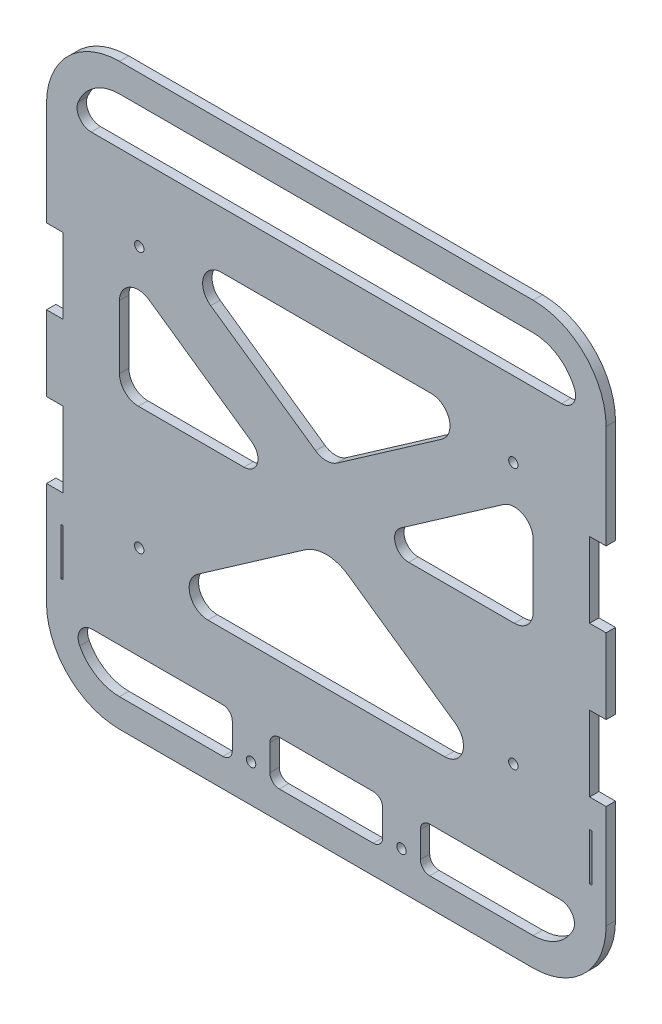
SolidWorks part; units mm, degrees
ref_plane "Front Plane" through (0, 0, 0) normal (0, 0, 1) x (1, 0, 0)
ref_plane "Top Plane" through (0, 0, 0) normal (0, 1, 0) x (1, 0, 0)
ref_plane "Right Plane" through (0, 0, 0) normal (1, 0, 0) x (0, 0, -1)
ref_plane "Plane1" through (0, 0, -676.275) normal (0, 0, 1) x (1, 0, 0)
sketch "Sketch1" plane through (0, 0, -676.275) normal (0, 0, 1) x (1, 0, 0)
  line L0 (94.488, -171.45) -> (94.488, -136.525)
  line L1 (94.488, -136.525) -> (88.9, -136.525)
  line L2 (88.9, -136.525) -> (88.9, -111.125)
  line L3 (88.9, -111.125) -> (94.488, -111.125)
  line L4 (94.488, -111.125) -> (94.488, -85.725)
  line L5 (94.488, -85.725) -> (88.9, -85.725)
  line L6 (88.9, -85.725) -> (88.9, -60.325)
  line L7 (88.9, -60.325) -> (94.488, -60.325)
  line L8 (94.488, -60.325) -> (94.488, -25.4)
  line L9 (69.85, -0.762) -> (-69.85, -0.762)
  line L10 (-94.488, -25.4) -> (-94.488, -60.325)
  line L11 (-94.488, -60.325) -> (-88.9, -60.325)
  line L12 (-88.9, -60.325) -> (-88.9, -85.725)
  line L13 (-88.9, -85.725) -> (-94.488, -85.725)
  line L14 (-94.488, -85.725) -> (-94.488, -111.125)
  line L15 (-94.488, -111.125) -> (-88.9, -111.125)
  line L16 (-88.9, -111.125) -> (-88.9, -136.525)
  line L17 (-88.9, -136.525) -> (-94.488, -136.525)
  line L18 (-94.488, -136.525) -> (-94.488, -171.45)
  line L19 (-69.85, -196.088) -> (69.85, -196.088)
  line L20 (7.2646, -112.3283) -> (43.598, -137.6665)
  line L21 (39.9657, -149.225) -> (-39.9657, -149.225)
  line L22 (-43.598, -137.6665) -> (-7.2646, -112.3283)
  line L23 (39.0453, -56.8078) -> (3.6323, -81.5041)
  line L24 (-3.6323, -81.5041) -> (-39.0453, -56.8078)
  line L25 (-35.4129, -45.2493) -> (35.4129, -45.2493)
  line L26 (69.85, -70.7201) -> (69.85, -92.075)
  line L27 (63.5, -98.425) -> (27.8268, -98.425)
  line L28 (25.1025, -89.7561) -> (59.8677, -65.5116)
  line L29 (-59.8677, -65.5116) -> (-25.1025, -89.7561)
  line L30 (-27.8268, -98.425) -> (-63.5, -98.425)
  line L31 (-69.85, -92.075) -> (-69.85, -70.7201)
  line L32 (0, -0.762) -> (0, -196.088) construction
  line L33 (-63.1655, -51.5993) -> (63.1655, -51.5993) construction
  line L34 (-63.1655, -51.5993) -> (-63.1655, -139.7) construction
  line L35 (-63.1655, -139.7) -> (63.1655, -139.7) construction
  line L36 (63.1655, -51.5993) -> (63.1655, -139.7) construction
  line L37 (-63.1655, -51.5993) -> (63.1655, -139.7) construction
  line L38 (-63.1655, -139.7) -> (63.1655, -51.5993) construction
  line L39 (-69.85, -186.563) -> (-34.925, -186.563)
  line L40 (-79.0397, -171.45) -> (-34.925, -171.45)
  line L41 (-25.4, -183.388) -> (25.4, -183.388) construction
  line L42 (69.85, -10.287) -> (-69.85, -10.287)
  line L43 (-31.75, -174.625) -> (-31.75, -183.388)
  line L44 (-19.05, -183.388) -> (-19.05, -174.625)
  line L45 (19.05, -174.625) -> (19.05, -183.388)
  line L46 (31.75, -174.625) -> (31.75, -183.388)
  line L47 (-15.875, -171.45) -> (15.875, -171.45)
  line L48 (34.925, -171.45) -> (79.0397, -171.45)
  line L49 (-15.875, -186.563) -> (15.875, -186.563)
  line L50 (-69.85, -186.563) -> (69.85, -186.563) construction
  line L51 (34.925, -186.563) -> (69.85, -186.563)
  line L52 (-79.4117, -26.1993) -> (79.4117, -26.1993)
  line L53 (-89.6493, -146.05) -> (-89.6493, -161.925)
  line L54 (88.9, -146.05) -> (89.6493, -146.05)
  line L55 (88.9, -146.05) -> (88.9, -161.925)
  line L56 (88.9, -161.925) -> (89.6493, -161.925)
  line L57 (89.6493, -146.05) -> (89.6493, -161.925)
  line L58 (-88.9, -161.925) -> (-89.6493, -161.925)
  line L59 (-88.9, -146.05) -> (-88.9, -161.925)
  line L60 (-88.9, -146.05) -> (-89.6493, -146.05)
  circle A0 centre (63.1655, -139.7) radius 1.5875
  circle A1 centre (-83.82, -84.8367) radius 1.5875 construction
  circle A2 centre (-63.1655, -51.5993) radius 1.5875
  circle A3 centre (25.4, -183.388) radius 1.5875
  arc A4 (69.85, -196.088) -> (94.488, -171.45) centre (69.85, -171.45) ccw
  arc A5 (94.488, -25.4) -> (69.85, -0.762) centre (69.85, -25.4) ccw
  arc A6 (-69.85, -0.762) -> (-94.488, -25.4) centre (-69.85, -25.4) ccw
  arc A7 (-94.488, -171.45) -> (-69.85, -196.088) centre (-69.85, -171.45) ccw
  circle A8 centre (-25.4, -183.388) radius 1.5875
  arc A9 (43.598, -137.6665) -> (39.9657, -149.225) centre (39.9657, -142.875) cw
  arc A10 (-39.9657, -149.225) -> (-43.598, -137.6665) centre (-39.9657, -142.875) cw
  arc A11 (-7.2646, -112.3283) -> (7.2646, -112.3283) centre (0, -122.7454) cw
  circle A12 centre (-63.1655, -139.7) radius 1.5875
  arc A13 (3.6323, -81.5041) -> (-3.6323, -81.5041) centre (0, -76.2956) cw
  arc A14 (-35.4129, -45.2493) -> (-39.0453, -56.8078) centre (-35.4129, -51.5993) ccw
  arc A15 (35.4129, -45.2493) -> (39.0453, -56.8078) centre (35.4129, -51.5993) cw
  arc A16 (69.85, -92.075) -> (63.5, -98.425) centre (63.5, -92.075) cw
  arc A17 (27.8268, -98.425) -> (25.1025, -89.7561) centre (27.8268, -93.6625) cw
  arc A18 (59.8677, -65.5116) -> (69.85, -70.7201) centre (63.5, -70.7201) cw
  arc A19 (-25.1025, -89.7561) -> (-27.8268, -98.425) centre (-27.8268, -93.6625) cw
  arc A20 (-63.5, -98.425) -> (-69.85, -92.075) centre (-63.5, -92.075) cw
  arc A21 (-69.85, -70.7201) -> (-59.8677, -65.5116) centre (-63.5, -70.7201) cw
  circle A22 centre (63.1655, -51.5993) radius 1.5875
  circle A23 centre (-63.1655, -51.5993) radius 12.7 construction
  arc A24 (-83.2682, -178.4038) -> (-69.85, -186.563) centre (-69.85, -171.45) ccw
  arc A25 (69.85, -186.563) -> (83.2682, -178.4038) centre (69.85, -171.45) ccw
  arc A26 (-84.963, -171.45) -> (-69.85, -186.563) centre (-69.85, -171.45) ccw construction
  arc A27 (-83.2682, -178.4038) -> (-79.0397, -171.45) centre (-79.0397, -176.2125) cw
  arc A28 (69.85, -186.563) -> (84.963, -171.45) centre (69.85, -171.45) ccw construction
  arc A29 (83.2682, -178.4038) -> (79.0397, -171.45) centre (79.0397, -176.2125) ccw
  arc A30 (-31.75, -183.388) -> (-34.925, -186.563) centre (-34.925, -183.388) cw
  arc A31 (-19.05, -183.388) -> (-15.875, -186.563) centre (-15.875, -183.388) ccw
  arc A32 (83.8112, -19.6132) -> (69.85, -10.287) centre (69.85, -25.4) ccw
  arc A33 (-69.85, -10.287) -> (-83.8112, -19.6132) centre (-69.85, -25.4) ccw
  arc A34 (19.05, -183.388) -> (15.875, -186.563) centre (15.875, -183.388) cw
  arc A35 (31.75, -183.388) -> (34.925, -186.563) centre (34.925, -183.388) ccw
  arc A36 (31.75, -174.625) -> (34.925, -171.45) centre (34.925, -174.625) cw
  arc A37 (19.05, -174.625) -> (15.875, -171.45) centre (15.875, -174.625) ccw
  arc A38 (-19.05, -174.625) -> (-15.875, -171.45) centre (-15.875, -174.625) cw
  arc A39 (-31.75, -174.625) -> (-34.925, -171.45) centre (-34.925, -174.625) ccw
  arc A40 (-79.4117, -26.1993) -> (-83.8112, -19.6132) centre (-79.4117, -21.4368) cw
  arc A41 (79.4117, -26.1993) -> (83.8112, -19.6132) centre (79.4117, -21.4368) ccw
  arc A43 (-69.85, -10.287) -> (-84.963, -25.4) centre (-69.85, -25.4) ccw construction
  arc A44 (84.963, -25.4) -> (69.85, -10.287) centre (69.85, -25.4) ccw construction
  point P80 (0, -51.5993)
  point P96 (0, -183.388)
  dimension "D2" = 3.175
  dimension "D13" = 25.4
  dimension "D16" = 4.7625
  dimension "D24" = 3.175
  dimension "D25" = 3.175
  dimension "D26" = 3.175
  dimension "D27" = 25.4
  dimension "D28" = 6.35
  dimension "D29" = 4.7625
  dimension "D30" = 6.35
  dimension "D31" = 6.35
  dimension "D32" = 12.7
  dimension "D1" = 126.331
  dimension "D3" = 31.75
  dimension "D4" = 12.7
  dimension "D5" = 9.525
  dimension "D6" = 9.525
  dimension "D7" = 88.1007
  dimension "D8" = 9.525
  dimension "D9" = 9.525
  dimension "D10" = 19.05
  dimension "D11" = 19.05
  dimension "D12" = 6.35
  dimension "D14" = 22.225
  dimension "D17" = 12.7
  dimension "D18" = 50.8
  dimension "D20" = 12.7
  dimension "D21" = 12.7
  dimension "D22" = 6.35
  dimension "D23" = 6.35
  dimension "D33" = 9.525
  dimension "D34" = 0.7493
  dimension "D35" = 15.875
  dimension "D15" = 9.525
  dimension "D19" = 9.525
extrude "Boss-Extrude1" add sketch "Sketch1" against normal blind 3.175
